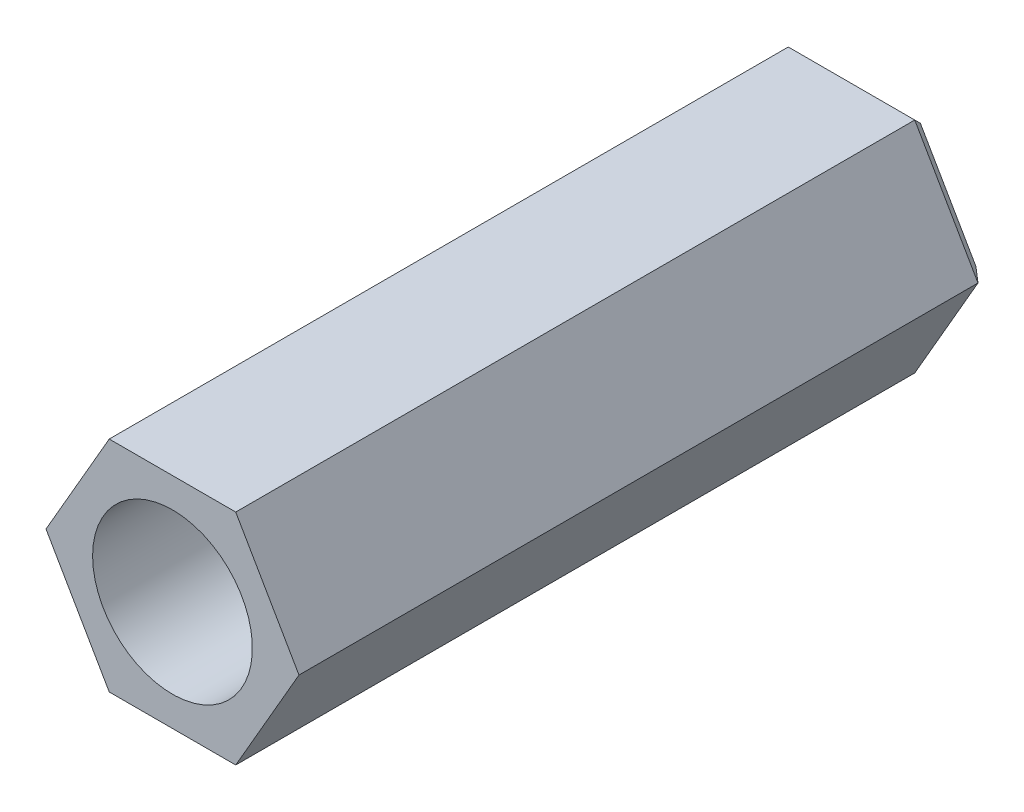
SolidWorks part; units mm, degrees
ref_plane "Plan de face" through (0, 0, 0) normal (0, 0, 1) x (1, 0, 0)
ref_plane "Plan de dessus" through (0, 0, 0) normal (0, 1, 0) x (1, 0, 0)
ref_plane "Plan de droite" through (0, 0, 0) normal (1, 0, 0) x (0, 0, -1)
sketch "Esquisse1" plane through (0, 0, 0) normal (0, 0, 1) x (1, 0, 0)
  line L1 (-1.1875, -2.0568) -> (1.1875, -2.0568)
  line L2 (1.1875, -2.0568) -> (2.375, 0)
  line L3 (2.375, 0) -> (1.1875, 2.0568)
  line L4 (1.1875, 2.0568) -> (-1.1875, 2.0568)
  line L5 (-1.1875, 2.0568) -> (-2.375, 0)
  line L6 (-2.375, 0) -> (-1.1875, -2.0568)
  circle A0 centre (0, 0) radius 2.0568 construction
  circle A1 centre (0, 0) radius 1.5
  dimension "D2" = 3
  dimension "D1" = 4.75
extrude "Boss.-Extru.1" add sketch "Esquisse1" along normal blind 13
chamfer "Chanfrein1" distance 0.25 angle 45 6 edges at (0, 2.0568, 0) (1.7812, 1.0284, 0) (1.7812, -1.0284, 0) (0, -2.0568, 0) (-1.7813, 1.0284, 0) (-1.7813, -1.0284, 0)
